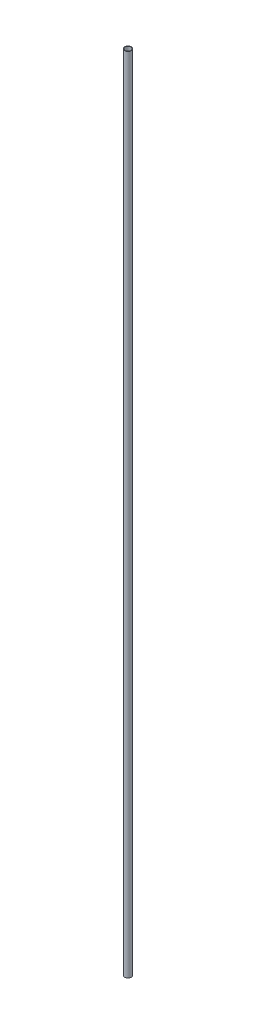
SolidWorks part; units mm, degrees
ref_plane "Front Plane" through (0, 0, 0) normal (0, 0, 1) x (1, 0, 0)
ref_plane "Top Plane" through (0, 0, 0) normal (0, 1, 0) x (1, 0, 0)
ref_plane "Right Plane" through (0, 0, 0) normal (1, 0, 0) x (0, 0, -1)
sketch "Sketch1" plane through (0, 0, 0) normal (0, 1, 0) x (1, 0, 0)
  circle A0 centre (0, 0) radius 4
  circle A1 centre (0, 0) radius 3.5
  dimension "D1" = 8
  dimension "D2" = 7
extrude "Boss-Extrude1" add sketch "Sketch1" along normal blind 955.88
